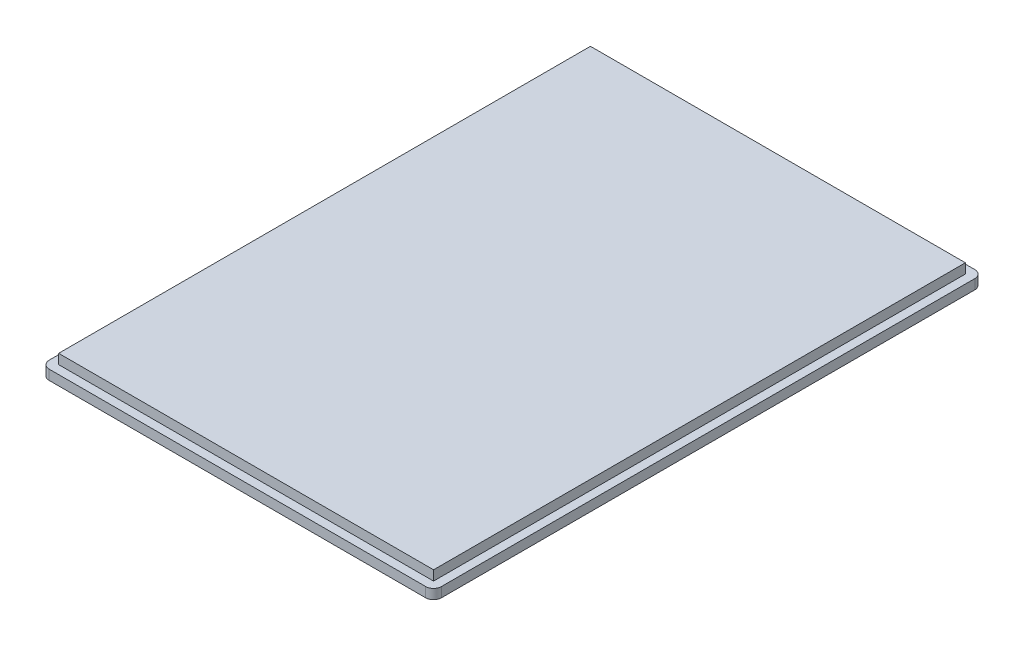
SolidWorks part; units mm, degrees
ref_plane "Front Plane" through (0, 0, 0) normal (0, 0, 1) x (1, 0, 0)
ref_plane "Top Plane" through (0, 0, 0) normal (0, 1, 0) x (1, 0, 0)
ref_plane "Right Plane" through (0, 0, 0) normal (1, 0, 0) x (0, 0, -1)
sketch "Sketch1" plane through (0, 0, 0) normal (0, 1, 0) x (1, 0, 0)
  line L1 (0, 0) -> (127, 0)
  line L2 (0, 0) -> (0, 177.8)
  line L3 (0, 177.8) -> (127, 177.8)
  line L4 (127, 0) -> (127, 177.8)
  dimension "D1" = 127
  dimension "D2" = 177.8
extrude "Boss-Extrude1" add sketch "Sketch1" along normal blind 3.175
fillet "Fillet1" radius 2.54 4 edges at (0, 1.5875, -177.8) (127, 1.5875, -177.8) (127, 1.5875, 0) (0, 1.5875, 0)
sketch "Sketch2" plane through (0, 3.175, 0) normal (0, 1, 0) x (1, 0, 0)
  line L0 (124.46, 177.8) -> (2.54, 177.8) construction
  line L1 (2.794, 175.006) -> (124.206, 175.006)
  line L2 (2.794, 175.006) -> (2.794, 2.794)
  line L3 (2.794, 2.794) -> (124.206, 2.794)
  line L4 (124.206, 175.006) -> (124.206, 2.794)
  line L5 (127, 2.54) -> (127, 175.26) construction
  line L6 (0, 175.26) -> (0, 2.54) construction
  line L7 (2.54, 0) -> (124.46, 0) construction
  point P10 (0, 0)
  dimension "D1" = 2.794
  dimension "D2" = 2.794
  dimension "D3" = 2.794
  dimension "D4" = 2.794
extrude "Boss-Extrude2" add sketch "Sketch2" along normal blind 3.175
